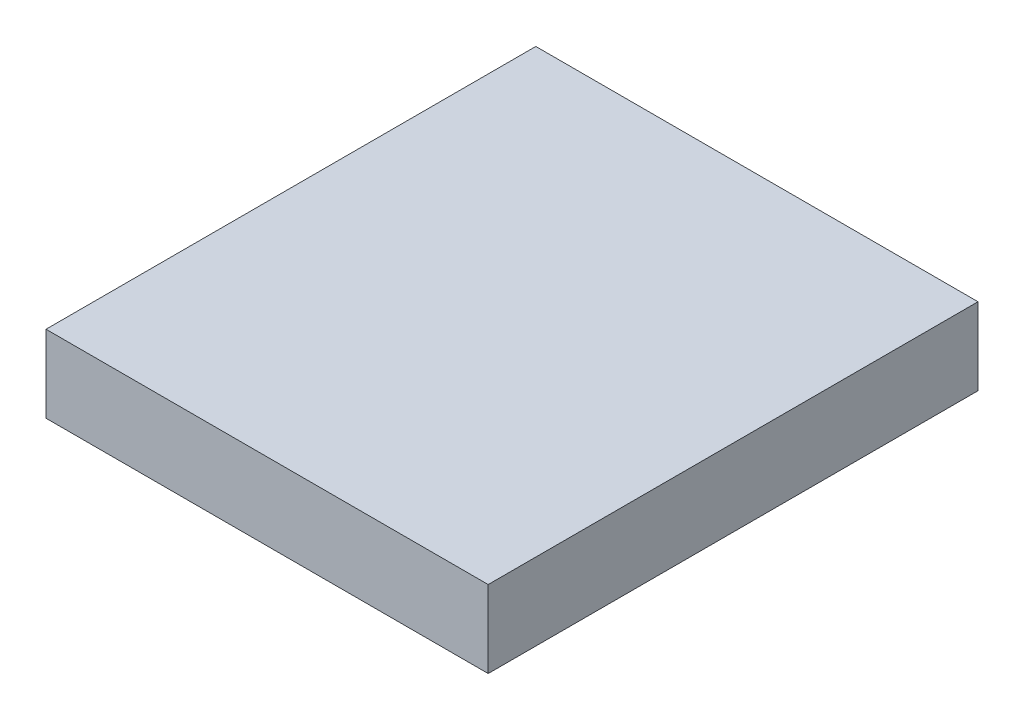
SolidWorks part; units mm, degrees
ref_plane "Front Plane" through (0, 0, 0) normal (0, 0, 1) x (1, 0, 0)
ref_plane "Top Plane" through (0, 0, 0) normal (0, 1, 0) x (1, 0, 0)
ref_plane "Right Plane" through (0, 0, 0) normal (1, 0, 0) x (0, 0, -1)
sketch "Sketch1" plane through (0, 0, 0) normal (0, 1, 0) x (1, 0, 0)
  line L1 (-25.1978, 9.329) -> (24.3322, 9.329)
  line L2 (-25.1978, 9.329) -> (-25.1978, -45.535)
  line L3 (-25.1978, -45.535) -> (24.3322, -45.535)
  line L4 (24.3322, 9.329) -> (24.3322, -45.535)
  dimension "D1" = 49.53
  dimension "D2" = 54.864
extrude "Boss-Extrude1" add sketch "Sketch1" along normal blind 8.636
